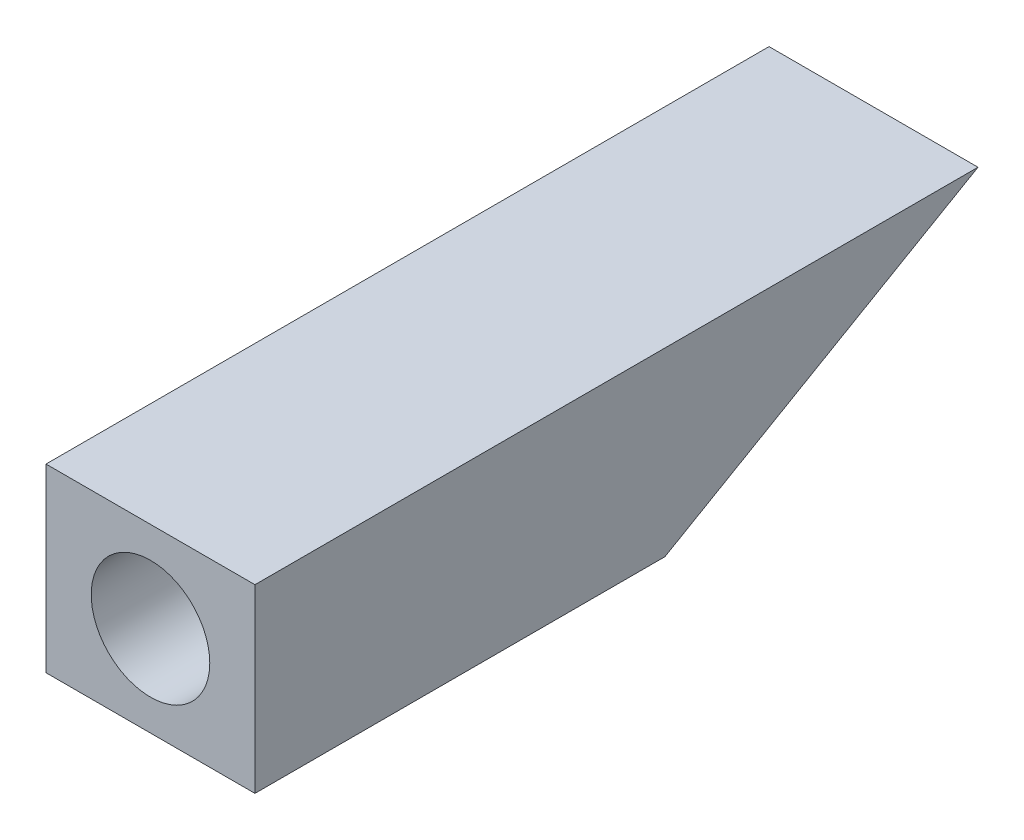
SolidWorks part; units mm, degrees
ref_plane "Front Plane" through (0, 0, 0) normal (0, 0, 1) x (1, 0, 0)
ref_plane "Top Plane" through (0, 0, 0) normal (0, 1, 0) x (1, 0, 0)
ref_plane "Right Plane" through (0, 0, 0) normal (1, 0, 0) x (0, 0, -1)
sketch "Sketch1" plane through (0, 0, 0) normal (0, 0, 1) x (1, 0, 0)
  line L1 (-3.6703, -3.175) -> (3.6703, -3.175)
  line L2 (-3.6703, -3.175) -> (-3.6703, 3.175)
  line L3 (-3.6703, 3.175) -> (3.6703, 3.175)
  line L4 (3.6703, -3.175) -> (3.6703, 3.175)
  line L5 (-3.6703, -3.175) -> (3.6703, 3.175) construction
  line L6 (-3.6703, 3.175) -> (3.6703, -3.175) construction
  point P0 (0, 0)
  dimension "D1" = 6.35
  dimension "D2" = 7.3406
extrude "Boss-Extrude1" add sketch "Sketch1" along normal blind 25.4
sketch "Sketch2" plane through (3.6703, 0, 0) normal (1, 0, 0) x (0, 0, -1)
  line L0 (0, 3.175) -> (-10.9985, -3.175)
  line L1 (-25.4, -3.175) -> (0, -3.175) construction
  line L2 (-10.9985, -3.175) -> (0, -3.175)
  line L3 (0, -3.175) -> (0, 3.175)
  dimension "D1" = 30
extrude "Cut-Extrude1" cut sketch "Sketch2" against normal blind 7.3406
sketch "Sketch3" plane through (0, 0, 25.4) normal (0, 0, 1) x (1, 0, 0)
  line L0 (-3.6703, 3.175) -> (3.6703, -3.175) construction
  circle A0 centre (0, 0) radius 2.0828
  dimension "D1" = 4.1656
extrude "Cut-Extrude2" cut sketch "Sketch3" against normal blind 25.4
